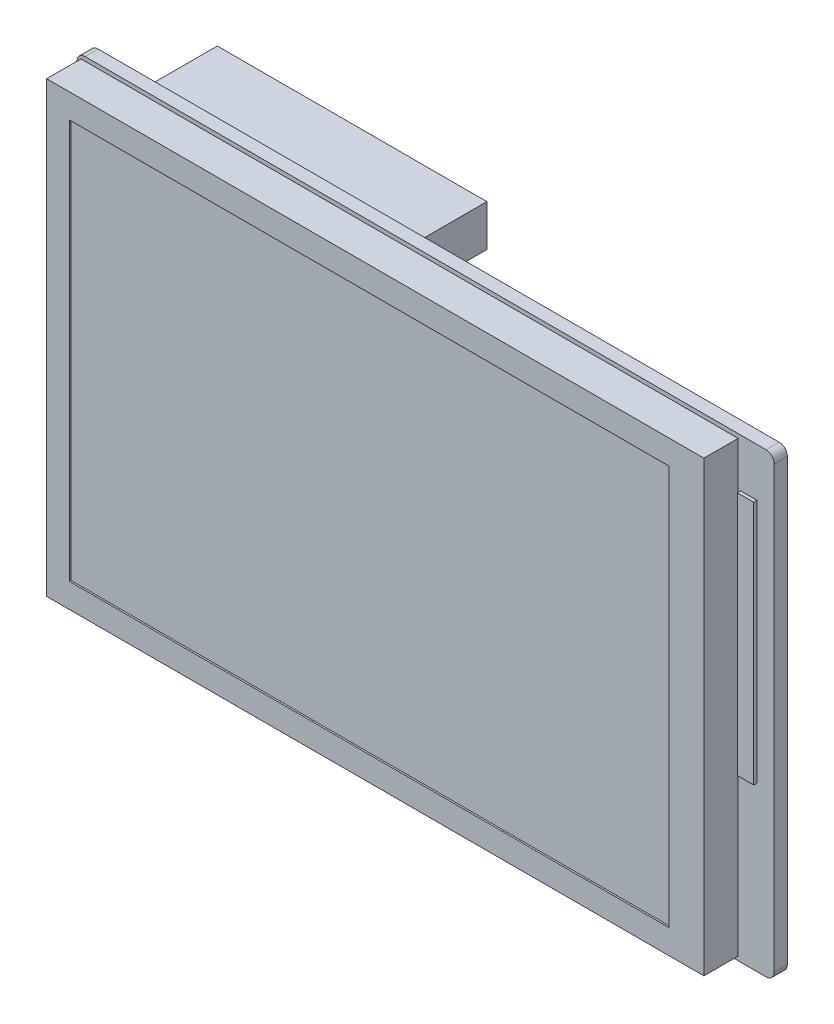
SolidWorks part; units mm, degrees
ref_plane "Front Plane" through (0, 0, 0) normal (0, 0, 1) x (1, 0, 0)
ref_plane "Top Plane" through (0, 0, 0) normal (0, 1, 0) x (1, 0, 0)
ref_plane "Right Plane" through (0, 0, 0) normal (1, 0, 0) x (0, 0, -1)
sketch "Sketch1" plane through (0, 0, 0) normal (0, 0, 1) x (1, 0, 0)
  line L0 (1, 0) -> (84.42, 0)
  line L1 (85.42, 1) -> (85.42, 54.92)
  line L2 (84.42, 55.92) -> (1, 55.92)
  line L3 (0, 54.92) -> (0, 1)
  arc A0 (84.42, 0) -> (85.42, 1) centre (84.42, 1) ccw
  arc A1 (85.42, 54.92) -> (84.42, 55.92) centre (84.42, 54.92) ccw
  arc A2 (1, 55.92) -> (0, 54.92) centre (1, 54.92) ccw
  arc A3 (0, 1) -> (1, 0) centre (1, 1) ccw
extrude "PCB" add sketch "Sketch1" along normal blind 1.6
ref_plane "Plane_z1_6" through (0, 0, 1.6) normal (0, 0, 1) x (1, 0, 0)
sketch "Sketch2" plane through (0, 0, 1.6) normal (0, 0, 1) x (1, 0, 0)
  line L1 (81.3, 20) -> (83.3, 20)
  line L2 (81.3, 20) -> (81.3, 50)
  line L3 (81.3, 50) -> (83.3, 50)
  line L4 (83.3, 20) -> (83.3, 50)
extrude "Body00" add sketch "Sketch2" along normal blind 0.4
sketch "Sketch3" plane through (0, 0, 1.6) normal (0, 0, 1) x (1, 0, 0)
  line L1 (0.5, 0.5) -> (81, 0.5)
  line L2 (0.5, 0.5) -> (0.5, 55.42)
  line L3 (0.5, 55.42) -> (81, 55.42)
  line L4 (81, 0.5) -> (81, 55.42)
extrude "Body01" add sketch "Sketch3" along normal blind 4.2
sketch "Sketch4" plane through (0, 0, 0) normal (0, 0, 1) x (1, 0, 0)
  line L1 (50.5, 0) -> (56.5, 0)
  line L2 (50.5, 0) -> (50.5, 12)
  line L3 (50.5, 12) -> (56.5, 12)
  line L4 (56.5, 0) -> (56.5, 12)
extrude "Under00" add sketch "Sketch4" against normal blind 5
sketch "Sketch5" plane through (0, 0, 0) normal (0, 0, 1) x (1, 0, 0)
  line L1 (24.5, -0.5) -> (39.5, -0.5)
  line L2 (24.5, -0.5) -> (24.5, 11)
  line L3 (24.5, 11) -> (39.5, 11)
  line L4 (39.5, -0.5) -> (39.5, 11)
extrude "Under01" add sketch "Sketch5" against normal blind 5.6
sketch "Sketch6" plane through (0, 0, 0) normal (0, 0, 1) x (1, 0, 0)
  line L1 (7.1, 49.96) -> (40.12, 49.96)
  line L2 (7.1, 49.96) -> (7.1, 55.04)
  line L3 (7.1, 55.04) -> (40.12, 55.04)
  line L4 (40.12, 49.96) -> (40.12, 55.04)
extrude "Under02" add sketch "Sketch6" against normal blind 8.5
sketch "Sketch7" plane through (0, 0, 0) normal (0, 1, 0) x (1, 0, 0)
  circle A0 centre (53.5, 2.5) radius 2.5
extrude "Side0_Audio_jack_nose" add sketch "Sketch7" against normal blind 2.5
sketch "Sketch8" plane through (0, 0, 0) normal (0, 1, 0) x (1, 0, 0)
  circle A0 centre (53.5, 2.5) radius 1.75
extrude "SideBore0_Audio_jack_nose" cut sketch "Sketch8" against normal blind 2.5
ref_plane "Plane_y10_5" through (0, 10.5, 0) normal (0, 1, 0) x (1, 0, 0)
sketch "Sketch9" plane through (0, 10.5, 0) normal (0, 1, 0) x (1, 0, 0)
  line L1 (25, 5.05) -> (39, 5.05)
  line L2 (25, 5.05) -> (25, 0.55)
  line L3 (25, 0.55) -> (39, 0.55)
  line L4 (39, 5.05) -> (39, 0.55)
extrude "Cut00" cut sketch "Sketch9" against normal blind 11
sketch "Sketch10" plane through (0, 0, 0) normal (0, 0, 1) x (1, 0, 0)
  line L1 (7.87, 50.73) -> (8.87, 50.73)
  line L2 (7.87, 50.73) -> (7.87, 51.73)
  line L3 (7.87, 51.73) -> (8.87, 51.73)
  line L4 (8.87, 50.73) -> (8.87, 51.73)
  line L6 (7.87, 53.27) -> (8.87, 53.27)
  line L7 (7.87, 53.27) -> (7.87, 54.27)
  line L8 (7.87, 54.27) -> (8.87, 54.27)
  line L9 (8.87, 53.27) -> (8.87, 54.27)
  line L11 (10.41, 50.73) -> (11.41, 50.73)
  line L12 (10.41, 50.73) -> (10.41, 51.73)
  line L13 (10.41, 51.73) -> (11.41, 51.73)
  line L14 (11.41, 50.73) -> (11.41, 51.73)
  line L16 (10.41, 53.27) -> (11.41, 53.27)
  line L17 (10.41, 53.27) -> (10.41, 54.27)
  line L18 (10.41, 54.27) -> (11.41, 54.27)
  line L19 (11.41, 53.27) -> (11.41, 54.27)
  line L21 (12.95, 50.73) -> (13.95, 50.73)
  line L22 (12.95, 50.73) -> (12.95, 51.73)
  line L23 (12.95, 51.73) -> (13.95, 51.73)
  line L24 (13.95, 50.73) -> (13.95, 51.73)
  line L26 (12.95, 53.27) -> (13.95, 53.27)
  line L27 (12.95, 53.27) -> (12.95, 54.27)
  line L28 (12.95, 54.27) -> (13.95, 54.27)
  line L29 (13.95, 53.27) -> (13.95, 54.27)
  line L31 (15.49, 50.73) -> (16.49, 50.73)
  line L32 (15.49, 50.73) -> (15.49, 51.73)
  line L33 (15.49, 51.73) -> (16.49, 51.73)
  line L34 (16.49, 50.73) -> (16.49, 51.73)
  line L36 (15.49, 53.27) -> (16.49, 53.27)
  line L37 (15.49, 53.27) -> (15.49, 54.27)
  line L38 (15.49, 54.27) -> (16.49, 54.27)
  line L39 (16.49, 53.27) -> (16.49, 54.27)
  line L41 (18.03, 50.73) -> (19.03, 50.73)
  line L42 (18.03, 50.73) -> (18.03, 51.73)
  line L43 (18.03, 51.73) -> (19.03, 51.73)
  line L44 (19.03, 50.73) -> (19.03, 51.73)
  line L46 (18.03, 53.27) -> (19.03, 53.27)
  line L47 (18.03, 53.27) -> (18.03, 54.27)
  line L48 (18.03, 54.27) -> (19.03, 54.27)
  line L49 (19.03, 53.27) -> (19.03, 54.27)
  line L51 (20.57, 50.73) -> (21.57, 50.73)
  line L52 (20.57, 50.73) -> (20.57, 51.73)
  line L53 (20.57, 51.73) -> (21.57, 51.73)
  line L54 (21.57, 50.73) -> (21.57, 51.73)
  line L56 (20.57, 53.27) -> (21.57, 53.27)
  line L57 (20.57, 53.27) -> (20.57, 54.27)
  line L58 (20.57, 54.27) -> (21.57, 54.27)
  line L59 (21.57, 53.27) -> (21.57, 54.27)
  line L61 (23.11, 50.73) -> (24.11, 50.73)
  line L62 (23.11, 50.73) -> (23.11, 51.73)
  line L63 (23.11, 51.73) -> (24.11, 51.73)
  line L64 (24.11, 50.73) -> (24.11, 51.73)
  line L66 (23.11, 53.27) -> (24.11, 53.27)
  line L67 (23.11, 53.27) -> (23.11, 54.27)
  line L68 (23.11, 54.27) -> (24.11, 54.27)
  line L69 (24.11, 53.27) -> (24.11, 54.27)
  line L71 (25.65, 50.73) -> (26.65, 50.73)
  line L72 (25.65, 50.73) -> (25.65, 51.73)
  line L73 (25.65, 51.73) -> (26.65, 51.73)
  line L74 (26.65, 50.73) -> (26.65, 51.73)
  line L76 (25.65, 53.27) -> (26.65, 53.27)
  line L77 (25.65, 53.27) -> (25.65, 54.27)
  line L78 (25.65, 54.27) -> (26.65, 54.27)
  line L79 (26.65, 53.27) -> (26.65, 54.27)
  line L81 (28.19, 50.73) -> (29.19, 50.73)
  line L82 (28.19, 50.73) -> (28.19, 51.73)
  line L83 (28.19, 51.73) -> (29.19, 51.73)
  line L84 (29.19, 50.73) -> (29.19, 51.73)
  line L86 (28.19, 53.27) -> (29.19, 53.27)
  line L87 (28.19, 53.27) -> (28.19, 54.27)
  line L88 (28.19, 54.27) -> (29.19, 54.27)
  line L89 (29.19, 53.27) -> (29.19, 54.27)
  line L91 (30.73, 50.73) -> (31.73, 50.73)
  line L92 (30.73, 50.73) -> (30.73, 51.73)
  line L93 (30.73, 51.73) -> (31.73, 51.73)
  line L94 (31.73, 50.73) -> (31.73, 51.73)
  line L96 (30.73, 53.27) -> (31.73, 53.27)
  line L97 (30.73, 53.27) -> (30.73, 54.27)
  line L98 (30.73, 54.27) -> (31.73, 54.27)
  line L99 (31.73, 53.27) -> (31.73, 54.27)
  line L101 (33.27, 50.73) -> (34.27, 50.73)
  line L102 (33.27, 50.73) -> (33.27, 51.73)
  line L103 (33.27, 51.73) -> (34.27, 51.73)
  line L104 (34.27, 50.73) -> (34.27, 51.73)
  line L106 (33.27, 53.27) -> (34.27, 53.27)
  line L107 (33.27, 53.27) -> (33.27, 54.27)
  line L108 (33.27, 54.27) -> (34.27, 54.27)
  line L109 (34.27, 53.27) -> (34.27, 54.27)
  line L111 (35.81, 50.73) -> (36.81, 50.73)
  line L112 (35.81, 50.73) -> (35.81, 51.73)
  line L113 (35.81, 51.73) -> (36.81, 51.73)
  line L114 (36.81, 50.73) -> (36.81, 51.73)
  line L116 (35.81, 53.27) -> (36.81, 53.27)
  line L117 (35.81, 53.27) -> (35.81, 54.27)
  line L118 (35.81, 54.27) -> (36.81, 54.27)
  line L119 (36.81, 53.27) -> (36.81, 54.27)
  line L121 (38.35, 50.73) -> (39.35, 50.73)
  line L122 (38.35, 50.73) -> (38.35, 51.73)
  line L123 (38.35, 51.73) -> (39.35, 51.73)
  line L124 (39.35, 50.73) -> (39.35, 51.73)
  line L126 (38.35, 53.27) -> (39.35, 53.27)
  line L127 (38.35, 53.27) -> (38.35, 54.27)
  line L128 (38.35, 54.27) -> (39.35, 54.27)
  line L129 (39.35, 53.27) -> (39.35, 54.27)
extrude "Cut01" cut sketch "Sketch10" against normal blind 8.5
ref_plane "Plane_z5_8" through (0, 0, 5.8) normal (0, 0, 1) x (1, 0, 0)
sketch "Sketch11" plane through (0, 0, 5.8) normal (0, 0, 1) x (1, 0, 0)
  line L1 (3.28, 3.48) -> (76.72, 3.48)
  line L2 (3.28, 3.48) -> (3.28, 52.44)
  line L3 (3.28, 52.44) -> (76.72, 52.44)
  line L4 (76.72, 3.48) -> (76.72, 52.44)
extrude "Cut02" cut sketch "Sketch11" against normal blind 0.2
sketch "Sketch12" plane through (0, 0, 1.6) normal (0, 0, 1) x (1, 0, 0)
  circle A0 centre (3.5, 3.5) radius 1.375
  circle A1 centre (3.5, 52.5) radius 1.375
  circle A2 centre (61.5, 3.5) radius 1.375
  circle A3 centre (61.5, 52.5) radius 1.375
extrude "Holes" cut sketch "Sketch12" against normal blind 1.6
equation "\"pcb_t\" = 1.6mm"
equation "\"D1@PCB\" = \"pcb_t\""
